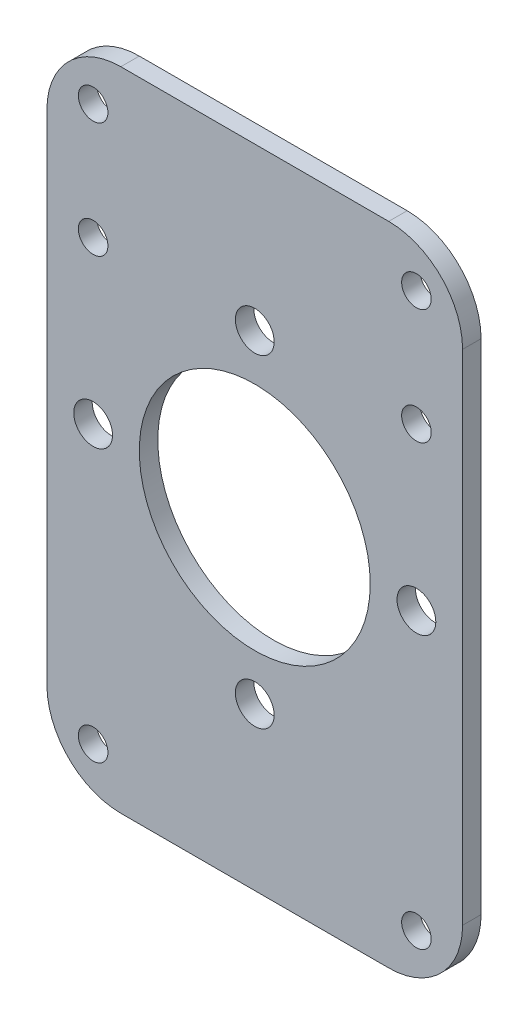
SolidWorks part; units mm, degrees
material "6061 合金"
ref_plane "正面" through (0, 0, 0) normal (0, 0, 1) x (1, 0, 0)
ref_plane "平面" through (0, 0, 0) normal (0, 1, 0) x (1, 0, 0)
ref_plane "右側面" through (0, 0, 0) normal (1, 0, 0) x (0, 0, -1)
sketch "ｽｹｯﾁ1" plane through (0, 0, 0) normal (0, 0, 1) x (1, 0, 0)
  line L0 (-17.5, 35) -> (-17.5, -35) construction
  line L1 (22.5, -35) -> (-22.5, -35)
  line L2 (22.5, -35) -> (22.5, 35)
  line L3 (22.5, 35) -> (-22.5, 35)
  line L4 (-22.5, -35) -> (-22.5, 35)
  line L5 (22.5, -35) -> (-22.5, 35) construction
  line L6 (22.5, 35) -> (-22.5, -35) construction
  line L7 (17.5, -17.5) -> (-17.5, -17.5) construction
  line L8 (17.5, -17.5) -> (17.5, 17.5) construction
  line L9 (17.5, 17.5) -> (-17.5, 17.5) construction
  line L10 (-17.5, -17.5) -> (-17.5, 17.5) construction
  line L11 (17.5, -17.5) -> (-17.5, 17.5) construction
  line L12 (17.5, 17.5) -> (-17.5, -17.5) construction
  line L13 (-17.5, -35) -> (17.5, 35) construction
  line L14 (17.5, 35) -> (17.5, -35) construction
  line L15 (17.5, -35) -> (-17.5, 35) construction
  circle A0 centre (-17.5, 0) radius 2.1
  circle A1 centre (0, 17.5) radius 2.1
  circle A2 centre (17.5, 0) radius 2.1
  circle A3 centre (0, -17.5) radius 2.1
  circle A4 centre (0, 0) radius 12.5
  circle A9 centre (-17.5, 30) radius 1.6
  circle A10 centre (17.5, 30) radius 1.6
  circle A11 centre (-17.5, -30) radius 1.6
  circle A12 centre (17.5, -30) radius 1.6
  circle A13 centre (-17.5, 17.5) radius 1.6
  circle A14 centre (17.5, 17.5) radius 1.6
  point P0 (0, 0)
  point P6 (0, 0)
  dimension "D3" = 4.2
  dimension "D4" = 25
  dimension "D5" = 3.2
  dimension "D9" = 5
  dimension "D10" = 5
  dimension "D11" = 5
  dimension "D1" = 35
  dimension "D2" = 70
  dimension "D6" = 45
  dimension "D8" = 5
extrude "ﾎﾞｽ - 押し出し1" add sketch "ｽｹｯﾁ1" along normal blind 2
fillet "ﾌｨﾚｯﾄ1" radius 8 4 edges at (-22.5, -35, 1) (22.5, -35, 1) (22.5, 35, 1) (-22.5, 35, 1)
